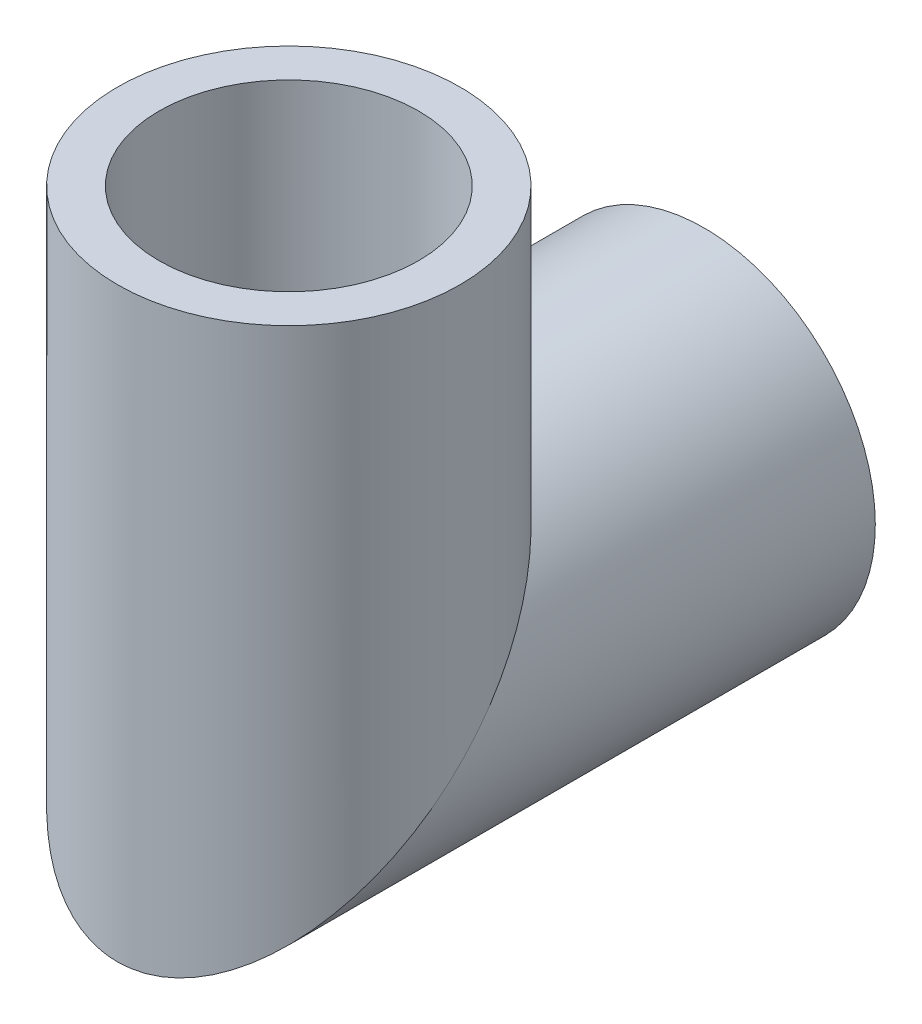
SolidWorks part; units mm, degrees
ref_plane "前视基准面" through (0, 0, 0) normal (0, 0, 1) x (1, 0, 0)
ref_plane "上视基准面" through (0, 0, 0) normal (0, 1, 0) x (1, 0, 0)
ref_plane "右视基准面" through (0, 0, 0) normal (1, 0, 0) x (0, 0, -1)
sketch "草图1" plane through (0, 0, 0) normal (0, 0, 1) x (1, 0, 0)
  circle A1 centre (0, 0) radius 16.5
  dimension "D2" = 33
sketch "草图2" plane through (0, 0, 0) normal (1, 0, 0) x (0, 0, -1)
  line L0 (0, 0) -> (-40, 0)
  line L1 (-40, 0) -> (-40, 40)
  dimension "D1" = 40
sweep "扫描1" add profiles "草图1" path "草图2"
sketch "草图3" plane through (0, 0, 0) normal (0, 0, -1) x (-1, 0, 0)
  circle A0 centre (0, 0) radius 12.5
  dimension "D1" = 25
sketch "草图4" plane through (0, 0, 0) normal (1, 0, 0) x (0, 0, -1)
  line L0 (0, 0) -> (-40, 0)
  line L1 (-56.5, -16.5) -> (-23.5, 16.5) construction
  line L2 (-40, 0) -> (-40, 40)
  line L3 (-23.5, 40) -> (-56.5, 40) construction
sweep "切除-扫描1" cut profiles "草图3" path "草图4"
